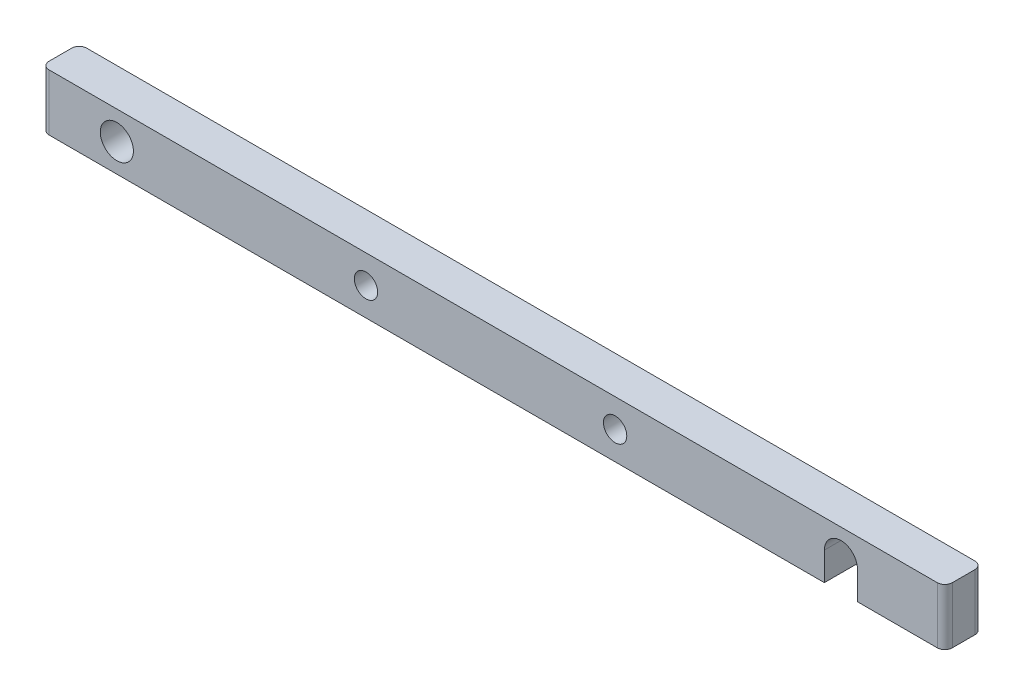
SolidWorks part; units mm, degrees
material "Balsa"
ref_plane "Front Plane" through (0, 0, 0) normal (0, 0, 1) x (1, 0, 0)
ref_plane "Top Plane" through (0, 0, 0) normal (0, 1, 0) x (1, 0, 0)
ref_plane "Right Plane" through (0, 0, 0) normal (1, 0, 0) x (0, 0, -1)
sketch "Sketch1" plane through (0, 0, 0) normal (0, 0, 1) x (1, 0, 0)
  line L1 (-152.4, -9.525) -> (152.4, -9.525)
  line L2 (-152.4, -9.525) -> (-152.4, 9.525)
  line L3 (-152.4, 9.525) -> (152.4, 9.525)
  line L4 (152.4, -9.525) -> (152.4, 9.525)
  line L5 (-152.4, -9.525) -> (152.4, 9.525) construction
  line L6 (-152.4, 9.525) -> (152.4, -9.525) construction
  point P0 (0, 0)
  dimension "D1" = 304.8
  dimension "D2" = 19.05
extrude "Boss-Extrude1" add sketch "Sketch1" along normal mid plane 12.7
sketch "Sketch2" plane through (0, 0, 6.35) normal (0, 0, 1) x (1, 0, 0)
  line L0 (117.348, 0) -> (117.348, -28.6373) construction
  line L1 (122.936, 0) -> (122.936, -28.6373)
  line L2 (111.76, 0) -> (111.76, -28.6373)
  line L4 (152.4, -9.525) -> (152.4, 9.525)
  line L5 (152.4, 9.525) -> (-152.4, 9.525)
  line L6 (-152.4, 9.525) -> (-152.4, -9.525)
  line L7 (-152.4, -9.525) -> (152.4, -9.525)
  line L8 (152.4, -9.525) -> (152.4, 9.525)
  line L9 (152.4, 9.525) -> (-152.4, 9.525)
  line L10 (-152.4, 9.525) -> (-152.4, -9.525)
  line L11 (-152.4, -9.525) -> (152.4, -9.525)
  circle A0 centre (-127, 0) radius 5.588
  circle A1 centre (-42.926, 0) radius 3.937
  circle A2 centre (41.148, 0) radius 3.937
  arc A3 (122.936, 0) -> (111.76, 0) centre (117.348, 0) ccw
  arc A4 (111.76, -28.6373) -> (122.936, -28.6373) centre (117.348, -28.6373) ccw
  point P12 (117.348, -14.3186)
  point P17 (117.348, -14.3186)
  dimension "D2" = 11.176
  dimension "D5" = 7.874
  dimension "D10" = 5.588
  dimension "D3" = 9.525
  dimension "D4" = 25.4
  dimension "D6" = 9.525
  dimension "D7" = 84.074
  dimension "D8" = 9.525
  dimension "D9" = 84.074
  dimension "D11" = 76.2
  dimension "D12" = 9.525
  dimension "D13" = 28.6373
  dimension "D1" = 0
extrude "Cut-Extrude1" cut sketch "Sketch2" against normal through all both and the other way through all
fillet "Fillet1" radius 2.54 4 edges at (-152.4, 0, -6.35) (-152.4, 0, 6.35) (152.4, 0, -6.35) (152.4, 0, 6.35)
